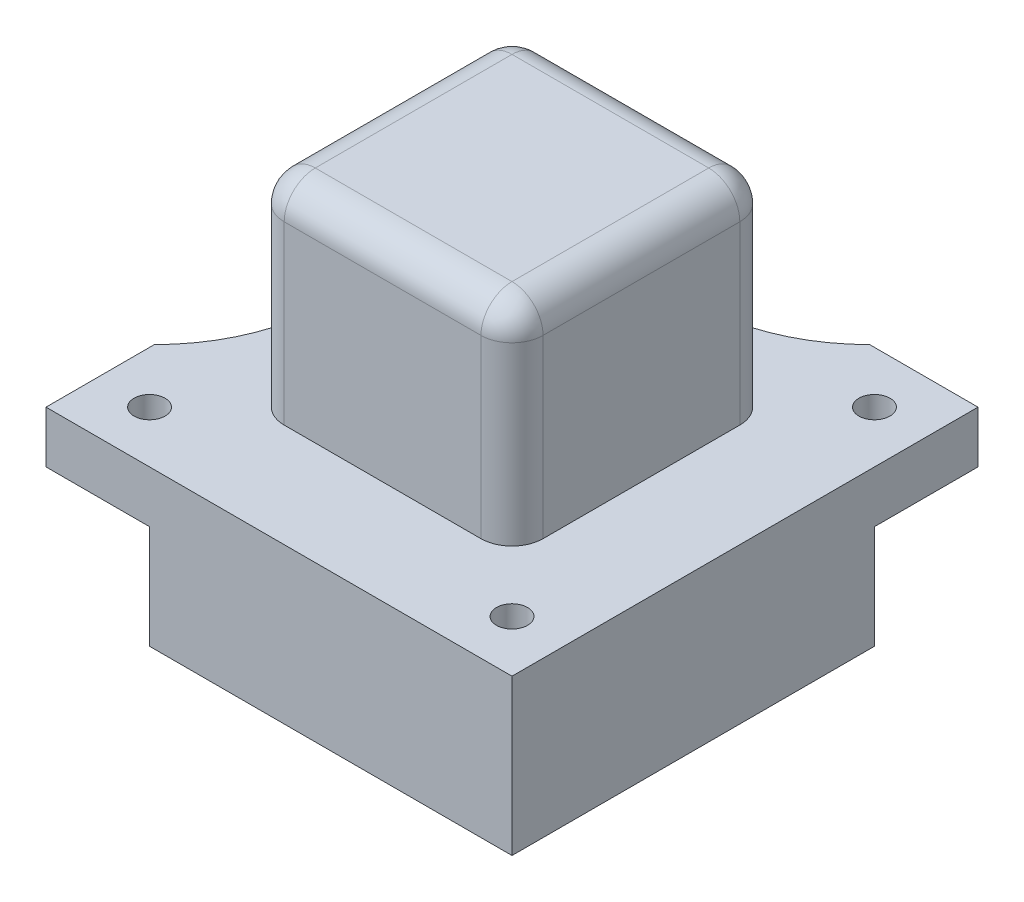
SolidWorks part; units mm, degrees
ref_plane "Front Plane" through (0, 0, 0) normal (0, 0, 1) x (1, 0, 0)
ref_plane "Top Plane" through (0, 0, 0) normal (0, 1, 0) x (1, 0, 0)
ref_plane "Right Plane" through (0, 0, 0) normal (1, 0, 0) x (0, 0, -1)
sketch "Sketch1" plane through (0, 0, 0) normal (0, 1, 0) x (1, 0, 0)
  line L1 (-21.8003, 27.3654) -> (23.1997, 27.3654)
  line L2 (-21.8003, 27.3654) -> (-21.8003, -17.6346)
  line L3 (-21.8003, -17.6346) -> (23.1997, -17.6346)
  line L4 (23.1997, 27.3654) -> (23.1997, -17.6346)
  dimension "D1" = 45
  dimension "D2" = 45
extrude "Boss-Extrude1" add sketch "Sketch1" along normal blind 15
sketch "Sketch2" plane through (0, 0, 0) normal (0, -1, 0) x (1, 0, 0)
  line L0 (-21.8003, 17.6346) -> (-11.8003, 17.6346)
  line L1 (-21.8003, 17.6346) -> (23.1997, 17.6346) construction
  line L2 (-11.8003, 17.6346) -> (-11.8003, -17.3654)
  line L3 (-11.8003, -17.3654) -> (23.1997, -17.3654)
  line L4 (23.1997, 17.6346) -> (23.1997, -27.3654) construction
  line L5 (23.1997, -17.3654) -> (23.1997, -27.3654)
  line L6 (23.1997, -27.3654) -> (-21.8003, -27.3654)
  line L7 (-21.8003, -27.3654) -> (-21.8003, 17.6346)
  dimension "D1" = 10
  dimension "D2" = 10
extrude "Cut-Extrude1" cut sketch "Sketch2" against normal blind 10
sketch "Sketch3" plane through (0, 10, 0) normal (0, -1, 0) x (1, 0, 0)
  line L0 (-11.3403, -27.3654) -> (12.7397, -27.3654)
  line L1 (-21.8003, 17.6346) -> (-21.8003, -27.3654) construction
  line L2 (-21.8003, 7.1746) -> (-21.8003, -16.9054)
  line L4 (-21.8003, -27.3654) -> (23.1997, -27.3654) construction
  arc A0 (-21.8003, 7.1746) -> (-21.8003, -16.9054) centre (-33.8019, -4.8654) cw
  arc A1 (-11.3403, -27.3654) -> (12.7397, -27.3654) centre (0.6997, -39.367) cw
  dimension "D5" = 17
  dimension "D6" = 17
extrude "Cut-Extrude2" cut sketch "Sketch3" against normal through all both and the other way through all
sketch "Sketch4" plane through (0, 10, 0) normal (0, -1, 0) x (1, 0, 0)
  line L0 (-21.8003, -17.4654) -> (-21.8003, -27.3654)
  line L1 (-21.8003, -16.9054) -> (-21.8003, -27.3654) construction
  line L2 (-21.8003, -27.3654) -> (-11.9003, -27.3654)
  line L3 (-21.8003, -27.3654) -> (-11.3403, -27.3654) construction
  arc A0 (-11.9003, -27.3654) -> (-21.8003, -17.4654) centre (-17.1102, -22.6753) ccw
  dimension "D3" = 7.01
sketch "Sketch5" plane through (0, 15, 0) normal (0, 1, 0) x (1, 0, 0)
  line L0 (23.1997, -17.6346) -> (23.1997, 27.3654) construction
  line L1 (-11.8003, 17.3654) -> (13.1997, 17.3654)
  line L2 (-11.8003, 17.3654) -> (-11.8003, -7.6346)
  line L3 (-11.8003, -7.6346) -> (13.1997, -7.6346)
  line L4 (13.1997, 17.3654) -> (13.1997, -7.6346)
  line L5 (-21.8003, -17.6346) -> (23.1997, -17.6346) construction
  dimension "D1" = 10
  dimension "D2" = 10
  dimension "D3" = 25
  dimension "D4" = 25
extrude "Boss-Extrude2" add sketch "Sketch5" along normal blind 20
fillet "Fillet1" radius 3 8 edges at (13.1997, 25, 7.6346) (13.1997, 35, -4.8654) (13.1997, 25, -17.3654) (0.6997, 35, -17.3654) (-11.8003, 25, -17.3654) (-11.8003, 35, -4.8654) (0.6997, 35, 7.6346) (-11.8003, 25, 7.6346)
sketch "Sketch6" plane through (0, 0, 0) normal (0, -1, 0) x (-1, 0, 0)
  line L0 (11.8003, -17.6346) -> (-23.1997, -17.6346) construction
  line L1 (-23.1997, -17.6346) -> (-23.1997, 17.3654) construction
  circle A0 centre (-0.6997, 4.8654) radius 6
  dimension "D1" = 22.5
  dimension "D2" = 22.5
  dimension "D3" = 12
extrude "Cut-Extrude4" cut sketch "Sketch6" against normal blind 28.9992
sketch "Sketch7" plane through (0, 28.9992, 0) normal (0, -1, 0) x (1, 0, 0)
  line L1 (-5.8003, -11.3654) -> (7.1997, -11.3654)
  line L2 (-5.8003, -11.3654) -> (-5.8003, 1.6346)
  line L3 (-5.8003, 1.6346) -> (7.1997, 1.6346)
  line L4 (7.1997, -11.3654) -> (7.1997, 1.6346)
  circle A1 centre (0.6997, -4.8654) radius 6 construction
  point P6 (7.1997, -4.8654)
  point P7 (0.6997, -11.3654)
  dimension "D1" = 0
  dimension "D2" = 0
  dimension "D3" = 13
  dimension "D4" = 13
extrude "Cut-Extrude5" cut sketch "Sketch7" along normal blind 13
fillet "Fillet2" radius 3 8 edges at (-5.8003, 22.4992, 1.6346) (0.6997, 28.9992, 1.6346) (7.1997, 22.4992, 1.6346) (7.1997, 22.4992, -11.3654) (-5.8003, 22.4992, -11.3654) (-5.8003, 28.9992, -4.8654) (0.6997, 28.9992, -11.3654) (7.1997, 28.9992, -4.8654)
sketch "Sketch8" plane through (0, 15, 0) normal (0, 1, 0) x (1, 0, 0)
  line L0 (-11.3403, 27.3654) -> (-21.8003, 27.3654) construction
  line L1 (-21.8003, 27.3654) -> (-21.8003, 16.9054) construction
  line L2 (23.1997, 27.3654) -> (12.7397, 27.3654) construction
  line L3 (23.1997, -17.6346) -> (23.1997, 27.3654) construction
  line L4 (-21.8003, -17.6346) -> (23.1997, -17.6346) construction
  line L5 (-21.8003, -7.1746) -> (-21.8003, -17.6346) construction
  circle A0 centre (-16.8003, 22.3654) radius 1.5
  circle A1 centre (18.1997, 22.3654) radius 1.5
  circle A2 centre (18.1997, -12.6346) radius 1.5
  circle A3 centre (-16.8003, -12.6346) radius 1.5
  dimension "D1" = 5
  dimension "D2" = 5
  dimension "D3" = 5
  dimension "D4" = 5
  dimension "D5" = 5
  dimension "D6" = 5
  dimension "D7" = 5
  dimension "D8" = 5
  dimension "D9" = 3
  dimension "D10" = 3
  dimension "D11" = 3
  dimension "D12" = 3
extrude "Cut-Extrude6" cut sketch "Sketch8" against normal through all both and the other way through all
sketch "Sketch9" plane through (0, 15, 0) normal (0, 1, 0) x (1, 0, 0)
  line L2 (-21.8003, 27.3654) -> (-11.5003, 27.3654)
  line L3 (-21.8003, 27.3654) -> (-21.8003, 17.0654)
  line L4 (-21.8003, 17.0654) -> (-11.5003, 17.0654)
  line L5 (-11.5003, 27.3654) -> (-11.5003, 17.0654)
  dimension "D1" = 10.3
  dimension "D2" = 10.3
extrude "Cut-Extrude7" cut sketch "Sketch9" against normal blind 2.7
sketch "Sketch10" plane through (0, 10, 0) normal (0, -1, 0) x (1, 0, 0)
  circle A0 centre (-16.8003, -22.3654) radius 6.85
  dimension "D1" = 13.7
extrude "Boss-Extrude3" add sketch "Sketch10" against normal blind 2.3
sketch "Sketch11" plane through (0, 10, 0) normal (0, -1, 0) x (1, 0, 0)
  line L0 (-21.4824, -27.3654) -> (-21.8003, -27.3654)
  line L1 (-21.8003, -27.3654) -> (-21.8003, -27.0475)
  arc A0 (-21.8003, -27.0475) -> (-21.4824, -27.3654) centre (-20.2144, -25.7795) ccw
extrude "Cut-Extrude8" cut sketch "Sketch11" against normal through all
sketch "Sketch12" plane through (0, 10, 0) normal (0, -1, 0) x (1, 0, 0)
  circle A0 centre (-17.1102, -22.6753) radius 1.5
  dimension "D1" = 3
extrude "Cut-Extrude9" cut sketch "Sketch12" against normal through all both and the other way through all
